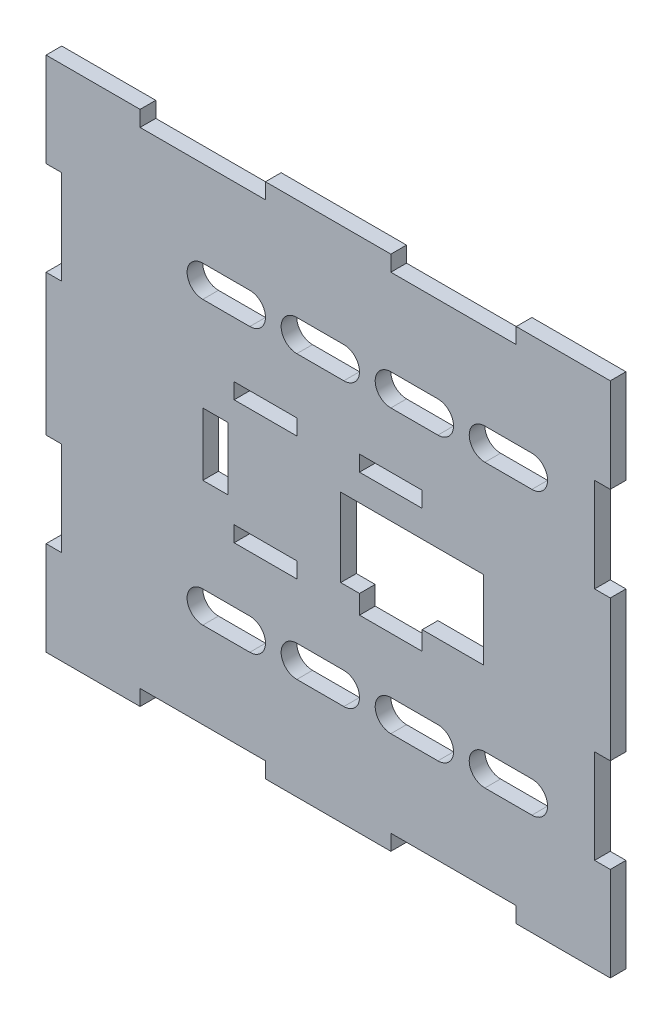
SolidWorks part; units mm, degrees
ref_plane "Front Plane" through (0, 0, 0) normal (0, 0, 1) x (1, 0, 0)
ref_plane "Top Plane" through (0, 0, 0) normal (0, 1, 0) x (1, 0, 0)
ref_plane "Right Plane" through (0, 0, 0) normal (1, 0, 0) x (0, 0, -1)
sketch "Sketch1" plane through (0, 0, 0) normal (0, 0, 1) x (1, 0, 0)
  line L0 (21.2424, 13.1936) -> (-33.7576, 13.1936)
  line L1 (-103.7576, 13.1936) -> (-73.7576, 13.1936)
  line L2 (-103.7576, 13.1936) -> (-103.7576, -16.8064)
  line L3 (-103.7576, -151.8064) -> (-73.7576, -151.8064)
  line L4 (51.2424, -24.3064) -> (51.2424, -114.3064)
  line L5 (-33.7576, -151.8064) -> (26.2424, -151.8064)
  line L6 (-73.7576, 13.1936) -> (-73.7576, 8.1936)
  line L7 (-73.7576, 8.1936) -> (-33.7576, 8.1936)
  line L8 (-33.7576, 13.1936) -> (-33.7576, 8.1936)
  line L9 (-103.7576, -46.8064) -> (-103.7576, -91.8064)
  line L10 (76.2424, -16.8064) -> (71.2424, -16.8064)
  line L11 (76.2424, -16.8064) -> (76.2424, -46.8064)
  line L12 (76.2424, -46.8064) -> (71.2424, -46.8064)
  line L13 (-103.7576, -16.8064) -> (-98.7576, -16.8064)
  line L14 (-103.7576, -121.8064) -> (-103.7576, -151.8064)
  line L15 (-103.7576, -46.8064) -> (-98.7576, -46.8064)
  line L16 (-98.7576, -16.8064) -> (-98.7576, -46.8064)
  line L17 (-103.7576, -91.8064) -> (-98.7576, -91.8064)
  line L18 (71.2424, -16.8064) -> (71.2424, -46.8064)
  line L19 (-103.7576, -121.8064) -> (-98.7576, -121.8064)
  line L20 (-98.7576, -91.8064) -> (-98.7576, -121.8064)
  line L21 (76.2424, -91.8064) -> (71.2424, -91.8064)
  line L22 (76.2424, -91.8064) -> (76.2424, -121.8064)
  line L23 (76.2424, -121.8064) -> (71.2424, -121.8064)
  line L24 (71.2424, -91.8064) -> (71.2424, -121.8064)
  line L25 (6.2424, 13.1936) -> (46.2424, 13.1936)
  line L26 (6.2424, 13.1936) -> (6.2424, 8.1936)
  line L27 (6.2424, 8.1936) -> (46.2424, 8.1936)
  line L28 (46.2424, 13.1936) -> (46.2424, 8.1936)
  line L29 (46.2424, -151.8064) -> (6.2424, -151.8064)
  line L30 (-73.7576, -151.8064) -> (-73.7576, -146.8064)
  line L31 (-73.7576, -146.8064) -> (-33.7576, -146.8064)
  line L32 (-33.7576, -151.8064) -> (-33.7576, -146.8064)
  line L33 (46.2424, -151.8064) -> (46.2424, -146.8064)
  line L34 (21.2424, 13.1936) -> (76.2424, 13.1936)
  line L35 (26.2424, 8.1936) -> (26.2424, -146.8064)
  line L36 (26.2424, -151.8064) -> (76.2424, -151.8064)
  line L37 (76.2424, 13.1936) -> (76.2424, -151.8064)
  line L38 (46.2424, -146.8064) -> (6.2424, -146.8064)
  line L39 (6.2424, -151.8064) -> (6.2424, -146.8064)
  line L40 (51.2424, -24.3064) -> (26.2424, -24.3064)
  line L41 (51.2424, -114.3064) -> (26.2424, -114.3064)
  line L42 (26.2424, -24.3064) -> (6.2424, -24.3064)
  line L43 (6.2424, -24.3064) -> (6.2424, -114.3064)
  line L44 (6.2424, -114.3064) -> (26.2424, -114.3064)
  line L45 (-8.7576, -29.3064) -> (-23.7576, -29.3064)
  line L46 (6.2424, -119.3064) -> (21.2424, -119.3064)
  line L47 (6.2424, -119.3064) -> (6.2424, -109.3064)
  line L48 (6.2424, -109.3064) -> (21.2424, -109.3064)
  line L49 (21.2424, -119.3064) -> (21.2424, -109.3064)
  line L50 (6.2424, -29.3064) -> (21.2424, -29.3064)
  line L51 (6.2424, -29.3064) -> (6.2424, -19.3064)
  line L52 (6.2424, -19.3064) -> (21.2424, -19.3064)
  line L53 (21.2424, -29.3064) -> (21.2424, -19.3064)
  line L54 (36.2424, -19.3064) -> (51.2424, -19.3064)
  line L55 (36.2424, -19.3064) -> (36.2424, -29.3064)
  line L56 (36.2424, -29.3064) -> (51.2424, -29.3064)
  line L57 (51.2424, -19.3064) -> (51.2424, -29.3064)
  line L58 (51.2424, -109.3064) -> (36.2424, -109.3064)
  line L59 (51.2424, -109.3064) -> (51.2424, -119.3064)
  line L60 (51.2424, -119.3064) -> (36.2424, -119.3064)
  line L61 (36.2424, -109.3064) -> (36.2424, -119.3064)
  line L62 (-23.7576, -19.3064) -> (-8.7576, -19.3064)
  line L63 (-8.7576, -119.3064) -> (-23.7576, -119.3064)
  line L64 (-23.7576, -109.3064) -> (-8.7576, -109.3064)
  line L65 (-38.7576, -19.3064) -> (-53.7576, -19.3064)
  line L66 (-53.7576, -19.3064) -> (-53.7576, -29.3064)
  line L67 (-53.7576, -29.3064) -> (-38.7576, -29.3064)
  line L68 (-38.7576, -109.3064) -> (-53.7576, -109.3064)
  line L69 (-53.7576, -109.3064) -> (-53.7576, -119.3064)
  line L70 (-53.7576, -119.3064) -> (-38.7576, -119.3064)
  circle A0 centre (51.2424, -24.3064) radius 5
  circle A1 centre (51.2424, -114.3064) radius 5
  circle A2 centre (36.2424, -114.3064) radius 5
  circle A3 centre (36.2424, -24.3064) radius 5
  circle A4 centre (21.2424, -24.3064) radius 5
  circle A5 centre (21.2424, -114.3064) radius 5
  circle A6 centre (6.2424, -24.3064) radius 5
  circle A7 centre (6.2424, -114.3064) radius 5
  circle A8 centre (-8.7576, -24.3064) radius 5
  circle A9 centre (-23.7576, -24.3064) radius 5
  circle A10 centre (-8.7576, -114.3064) radius 5
  circle A11 centre (-23.7576, -114.3064) radius 5
  circle A12 centre (-38.7576, -24.3064) radius 5
  circle A13 centre (-53.7576, -24.3064) radius 5
  circle A14 centre (-53.7576, -114.3064) radius 5
  circle A15 centre (-38.7576, -114.3064) radius 5
  dimension "D32" = 10
  dimension "D35" = 10
  dimension "D37" = 10
  dimension "D38" = 10
  dimension "D39" = 10
  dimension "D43" = 10
  dimension "D46" = 10
  dimension "D47" = 10
  dimension "D48" = 10
  dimension "D49" = 10
  dimension "D53" = 10
  dimension "D54" = 10
  dimension "D56" = 10
  dimension "D57" = 10
  dimension "D58" = 10
  dimension "D59" = 10
  dimension "D2" = 165
  dimension "D3" = 30
  dimension "D4" = 30
  dimension "D6" = 30
  dimension "D7" = 5
  dimension "D8" = 40
  dimension "D9" = 30
  dimension "D10" = 30
  dimension "D11" = 30
  dimension "D12" = 5
  dimension "D13" = 5
  dimension "D14" = 180
  dimension "D15" = 40
  dimension "D16" = 30
  dimension "D17" = 30
  dimension "D18" = 40
  dimension "D19" = 5
  dimension "D20" = 5
  dimension "D21" = 5
  dimension "D22" = 5
  dimension "D23" = 5
  dimension "D24" = 5
  dimension "D25" = 5
  dimension "D26" = 40
  dimension "D27" = 40
  dimension "D28" = 165
  dimension "D29" = 50
  dimension "D30" = 30
  dimension "D31" = 30
  dimension "D33" = 25
  dimension "D34" = 37.5
  dimension "D36" = 90
  dimension "D40" = 15
  dimension "D41" = 15
  dimension "D42" = 15
  dimension "D44" = 15
  dimension "D45" = 15
  dimension "D50" = 15
  dimension "D51" = 15
  dimension "D52" = 15
  dimension "D55" = 15
  dimension "D60" = 15
  dimension "D61" = 15
  dimension "D62" = 15
  dimension "D63" = 15
  dimension "D64" = 30
extrude "Boss-Extrude1" add sketch "Sketch1" along normal blind 5
sketch "Sketch2" plane through (0, 0, 0) normal (0, 0, -1) x (-1, 0, 0)
  line L0 (3.7576, -85.5564) -> (3.7576, -91.5564)
  line L1 (-24.2424, -151.8064) -> (103.7576, -151.8064)
  line L2 (-24.2424, 13.1936) -> (-24.2424, -47.0564)
  line L3 (-24.2424, 13.1936) -> (103.7576, 13.1936)
  line L4 (103.7576, -151.8064) -> (103.7576, 13.1936)
  line L5 (-24.2424, -47.0564) -> (-24.2424, -91.5564)
  line L6 (-24.2424, -91.5564) -> (-24.2424, -151.8064)
  line L7 (-24.2424, -47.0564) -> (45.7576, -47.0564)
  line L8 (9.7576, -91.5564) -> (-16.2424, -91.5564)
  line L9 (45.7576, -47.0564) -> (45.7576, -91.5564)
  line L10 (45.7576, -91.5564) -> (-24.2424, -91.5564)
  line L12 (9.7576, -85.5564) -> (-16.2424, -85.5564)
  line L13 (-16.2424, -91.5564) -> (-16.2424, -85.5564)
  line L14 (23.7576, -91.5564) -> (43.7576, -91.5564)
  line L15 (23.7576, -91.5564) -> (23.7576, -86.5564)
  line L16 (23.7576, -86.5564) -> (43.7576, -86.5564)
  line L17 (43.7576, -91.5564) -> (43.7576, -86.5564)
  line L18 (-16.2424, -47.0564) -> (3.7576, -47.0564)
  line L19 (-16.2424, -47.0564) -> (-16.2424, -52.0564)
  line L20 (-16.2424, -52.0564) -> (3.7576, -52.0564)
  line L21 (3.7576, -47.0564) -> (3.7576, -52.0564)
  line L22 (23.7576, -47.0564) -> (43.7576, -47.0564)
  line L23 (23.7576, -47.0564) -> (23.7576, -52.0564)
  line L24 (23.7576, -52.0564) -> (43.7576, -52.0564)
  line L25 (43.7576, -47.0564) -> (43.7576, -52.0564)
  line L26 (45.7576, -59.3064) -> (53.7576, -59.3064)
  line L27 (45.7576, -59.3064) -> (45.7576, -79.3064)
  line L28 (45.7576, -79.3064) -> (53.7576, -79.3064)
  line L29 (53.7576, -59.3064) -> (53.7576, -79.3064)
  line L30 (-21.2424, -60.5564) -> (-35.7424, -60.5564)
  line L31 (-21.2424, -60.5564) -> (-21.2424, -85.5564)
  line L32 (-21.2424, -85.5564) -> (-35.7424, -85.5564)
  line L33 (-35.7424, -60.5564) -> (-35.7424, -85.5564)
  line L35 (-76.2424, -151.8064) -> (103.7576, -151.8064)
  line L36 (-76.2424, -151.8064) -> (-76.2424, 13.1936)
  line L37 (-76.2424, 13.1936) -> (103.7576, 13.1936)
  line L38 (103.7576, -151.8064) -> (103.7576, 13.1936)
  line L39 (9.7576, -85.5564) -> (-21.2424, -85.5564)
  line L40 (9.7576, -85.5564) -> (9.7576, -60.5564)
  line L41 (9.7576, -60.5564) -> (-21.2424, -60.5564)
  line L42 (-21.2424, -85.5564) -> (-21.2424, -60.5564)
  line L44 (-24.2424, -91.5564) -> (-16.2424, -91.5564)
  dimension "D3" = 70
  dimension "D4" = 5
  dimension "D5" = 20
  dimension "D6" = 20
  dimension "D7" = 6
  dimension "D8" = 20
  dimension "D9" = 60.25
  dimension "D10" = 5
  dimension "D11" = 5
  dimension "D12" = 8
  dimension "D13" = 8
  dimension "D14" = 2
  dimension "D15" = 52
  dimension "D16" = 2
  dimension "D17" = 20
  dimension "D18" = 44.5
  dimension "D19" = 8
  dimension "D20" = 50
  dimension "D21" = 12.25
  dimension "D22" = 3
  dimension "D23" = 6
  dimension "D24" = 25
  dimension "D25" = 31
  dimension "D26" = 6
  dimension "D27" = 14.5
extrude "Cut-Extrude1" cut sketch "Sketch2" against normal blind 10 contours L21 L7 L19 L20 | L25 L7 L23 L24 | L10 L17 L16 L15 | L42 L39 L12 L40 L41 | L13 L8 L0 L12 | L29 L26 L27 L28 | L30 L33 L32 L5 | L32 L31 L30 L5
